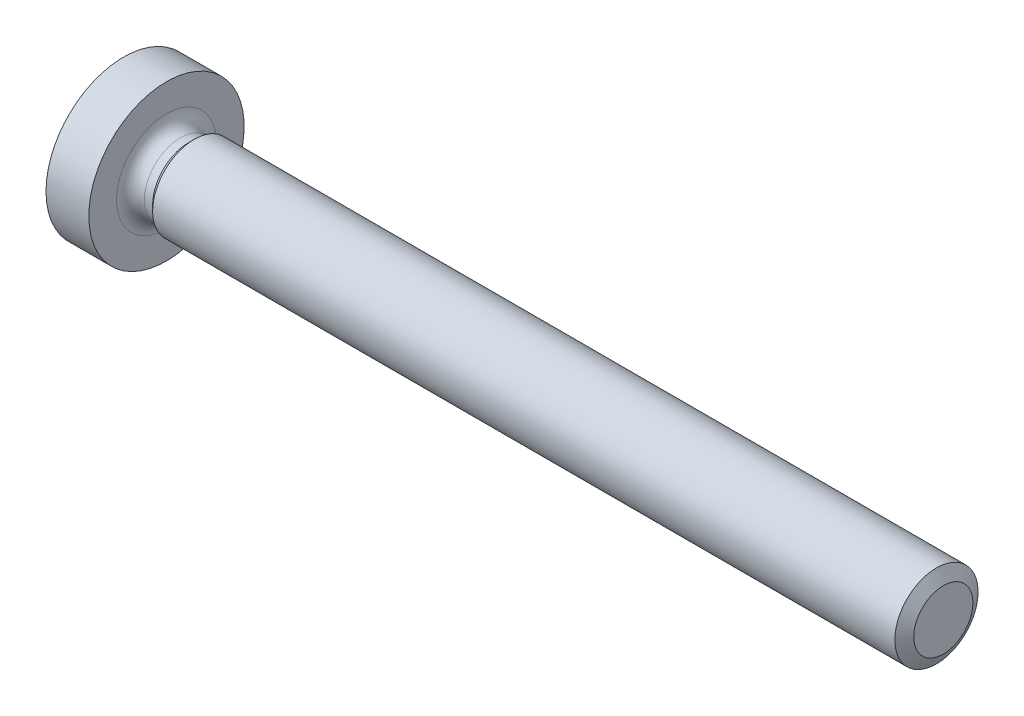
SolidWorks part; units mm, degrees
revolve "基体-旋转" add sketch "草图2" angle 360 about L0
sketch "草图2" plane through (0, 0, 0) normal (0, 0, 1) x (1, 0, 0)
  line L0 (-1.3318, 0) -> (6.5885, 0) construction
  line L1 (0, 0) -> (30.4, 0)
  line L2 (30.4, 0) -> (30.4, 1.5)
  line L3 (30.4, 1.5) -> (3.4, 1.5)
  line L4 (3.4, 1.5) -> (3.199, 1.299)
  line L5 (3.199, 1.299) -> (2.901, 1.299)
  line L6 (2.4, 1.8) -> (2.4, 2.8)
  line L7 (2.4, 2.8) -> (0.8575, 2.8)
  arc A0 (2.4, 1.8) -> (2.901, 1.299) centre (2.901, 1.8) ccw
  arc A1 (0, 0) -> (0.8575, 2.8) centre (5, 0) cw
  dimension "D3" = 5
  dimension "dk" = 5.6
  dimension "d" = 3
  dimension "l" = 28
  dimension "a" = 1
  dimension "D1" = 45
  dimension "D2" = 2.598
  dimension "da" = 3.6
  dimension "k" = 2.4
cosmetic thread "装饰螺纹线1" parameters "D1"=27, "D2"=2.598
ref_plane "前视" through (0, 0, 0) normal (0, 0, 1) x (1, 0, 0)
ref_plane "上视" through (0, 0, 0) normal (0, 1, 0) x (1, 0, 0)
ref_plane "右视" through (0, 0, 0) normal (1, 0, 0) x (0, 0, -1)
sketch "尺寸草图" plane through (0, 0, 0) normal (0, 0, 1) x (1, 0, 0)
  line L0 (0, 0) -> (28, 0)
  line L1 (0, 0) -> (0, 5.6)
  line L2 (28, 0) -> (28, 3.6)
  point P5 (0, 3)
  point P6 (27.5, 0)
  point P7 (1, 0)
  point P8 (2.4, 0)
  point P9 (23, 0)
  point P10 (3, 0)
  point P11 (26.2, 0)
  dimension "dk" = 5.6
  dimension "d" = 3
  dimension "l" = 28
  dimension "a" = 1
  dimension "da" = 3.6
  dimension "k" = 2.4
  dimension "P" = 0.5
  dimension "rf" = 5
  dimension "m" = 3
  dimension "h" = 1.8
sketch "草图3" plane through (0, 0, 0) normal (0, 0, 1) x (1, 0, 0)
  line L0 (30.1527, 1.5) -> (30.6527, 1.5)
  line L1 (30.6527, 1.5) -> (30.4, 1.067)
  line L2 (30.4, 1.067) -> (30.1527, 1.5)
  line L3 (30.4, 1.5) -> (3.4, 1.5) construction
  line L4 (30.4, -1.5) -> (30.4, 1.5) construction
  line L5 (-0.2428, 0) -> (7.1644, 0) construction
  line L6 (-1.3318, 0) -> (6.5885, 0) construction
  dimension "P" = 0.5
  dimension "D1" = 0.433
  dimension "D2" = 60
revolve "切除-旋转1" cut sketch "草图3" angle 360 about L5
sketch "草图5" plane through (0, 0, 0) normal (1, 0, 0) x (0, 0, -1)
  line L1 (0.25, 1.5) -> (-0.25, 1.5)
  line L2 (0.25, 1.5) -> (0.25, -1.5)
  line L3 (0.25, -1.5) -> (-0.25, -1.5)
  line L4 (-0.25, 1.5) -> (-0.25, -1.5)
  point P4 (0.25, 0)
  point P5 (0, 1.5)
  dimension "m" = 3
  dimension "D1" = 0.5
ref_plane "基准面1" through (1.8, 0, 0) normal (1, 0, 0) x (0, 0, -1)
pattern_linear "阵列(线性)1" [suppressed] count 55 spacing 0.5 along (1, 0, 0)
sketch "草图6" plane through (1.8, 0, 0) normal (1, 0, 0) x (0, 0, -1)
  point P0 (0, 0)
loft "切除-放样1" cut profiles "草图6", "草图5"
ref_plane "基准面2" through (0, 0, 0) normal (0, -0.7071, 0.7071) x (1, 0, 0)
mirror "镜向1" about plane through (0, 0, 0) normal (0, -0.7071, 0.7071) of "切除-放样1"
equation "\"l@草图2\" = \"l@尺寸草图\""
equation "\"dk@草图2\" = \"dk@尺寸草图\""
equation "\"k@草图2\" = \"k@尺寸草图\""
equation "\"D2@草图2\" = \"d@尺寸草图\"*0.866"
equation "\"a@草图2\" = \"a@尺寸草图\""
equation "\"D3@草图2\" = \"rf@尺寸草图\""
equation "\"d@草图2\" = \"d@尺寸草图\""
equation "\"da@草图2\" = \"da@尺寸草图\""
equation "\"D2@装饰螺纹线1\" = \"d@尺寸草图\"*0.866"
equation "\"D1@装饰螺纹线1\" = \"l@尺寸草图\"-\"a@尺寸草图\""
equation "\"P@草图3\" = \"P@尺寸草图\""
equation "\"D1@草图3\" = \"P@尺寸草图\"*0.866"
equation "\"h@基准面1\" = \"h@尺寸草图\""
equation "\"D1@草图5\" = \"P@尺寸草图\""
equation "\"m@草图5\" = \"m@尺寸草图\""
equation "\"D3@阵列(线性)1\" = \"P@尺寸草图\""
equation "\"D1@阵列(线性)1\" = (\"l@尺寸草图\"-\"a@尺寸草图\")/\"P@尺寸草图\"+1"
